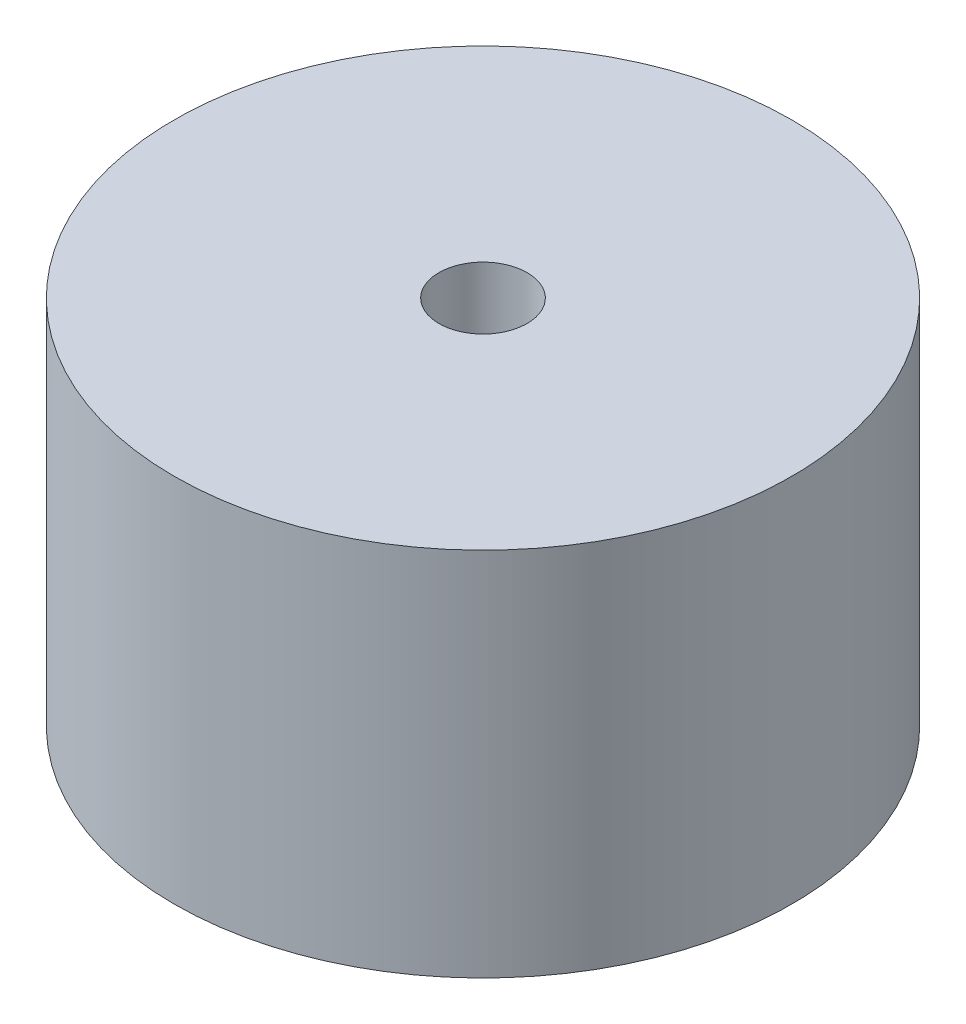
SolidWorks part; units mm, degrees
ref_plane "Plano frontal" through (0, 0, 0) normal (0, 0, 1) x (1, 0, 0)
ref_plane "Plano superior" through (0, 0, 0) normal (0, 1, 0) x (1, 0, 0)
ref_plane "Plano direito" through (0, 0, 0) normal (1, 0, 0) x (0, 0, -1)
sketch "Esboço1" plane through (0, 0, 0) normal (0, 1, 0) x (1, 0, 0)
  circle A0 centre (0.4897, 0) radius 17.5
  circle A1 centre (0.4897, 0) radius 2.5
  dimension "D1" = 35
  dimension "D2" = 5
extrude "Ressalto-extrusão1" add sketch "Esboço1" along normal blind 21
